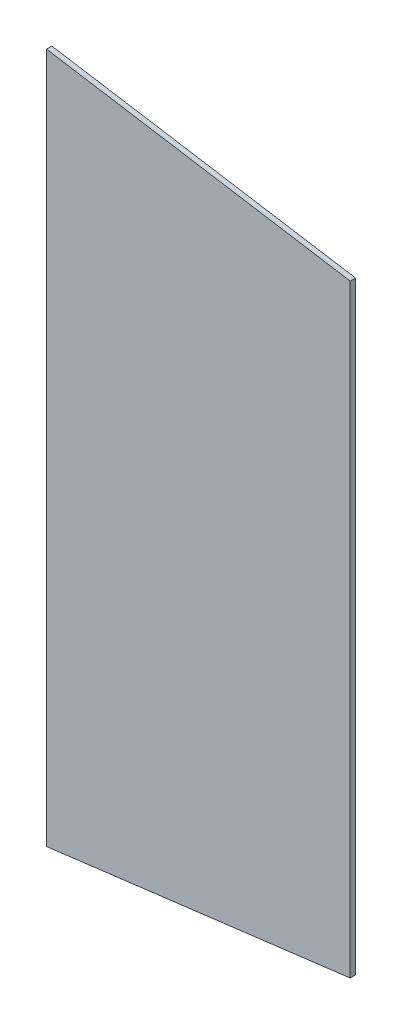
SolidWorks part; units mm, degrees
ref_plane "Front Plane" through (0, 0, 0) normal (0, 0, 1) x (1, 0, 0)
ref_plane "Top Plane" through (0, 0, 0) normal (0, 1, 0) x (1, 0, 0)
ref_plane "Right Plane" through (0, 0, 0) normal (1, 0, 0) x (0, 0, -1)
sketch "Sketch1" plane through (0, 0, 0) normal (0, 0, 1) x (1, 0, 0)
  line L0 (-69.7143, 63.0283) -> (-69.7143, -163.4844)
  line L1 (-69.7143, -163.4844) -> (-183.7143, -177.7344)
  line L2 (-183.7143, -177.7344) -> (-183.7143, 81.44)
  line L3 (-183.7143, 81.44) -> (-69.7143, 63.0283)
extrude "Boss-Extrude1" add sketch "Sketch1" along normal blind 2
